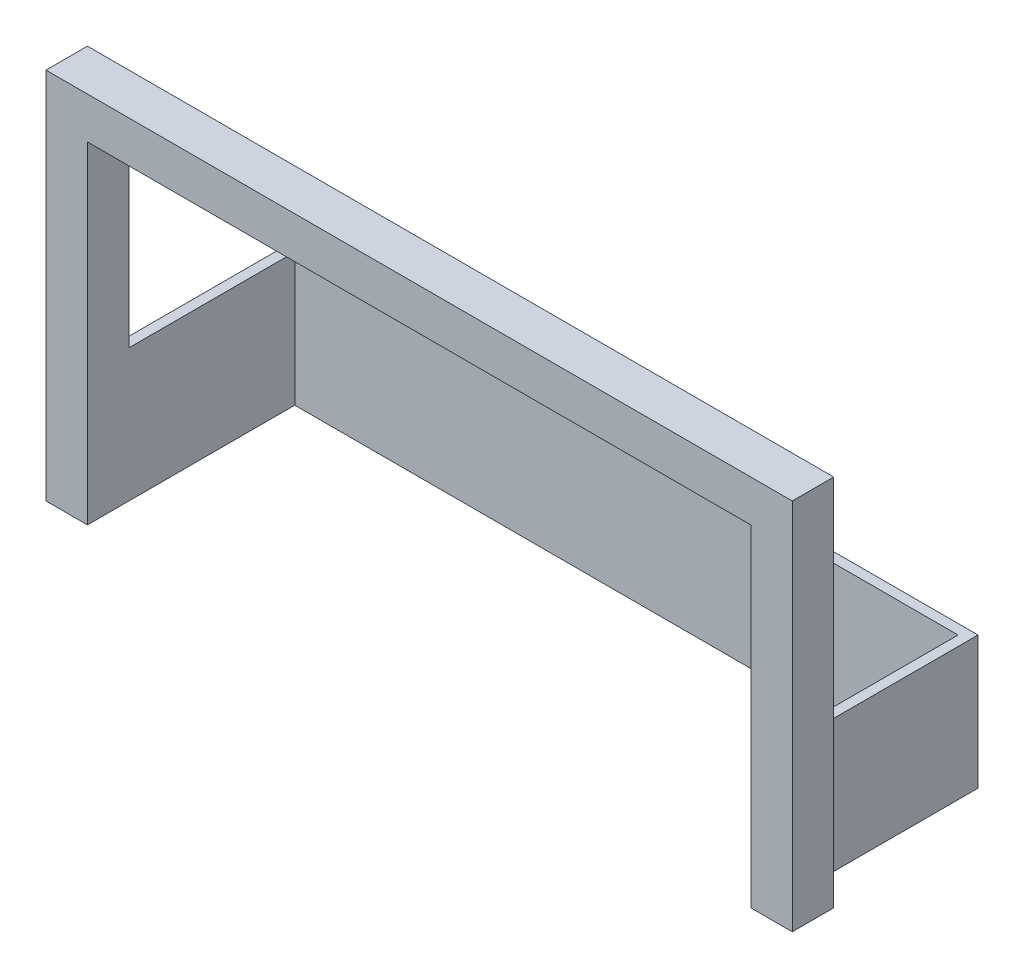
SolidWorks part; units mm, degrees
ref_plane "前视基准面" through (0, 0, 0) normal (0, 0, 1) x (1, 0, 0)
ref_plane "上视基准面" through (0, 0, 0) normal (0, 1, 0) x (1, 0, 0)
ref_plane "右视基准面" through (0, 0, 0) normal (1, 0, 0) x (0, 0, -1)
sketch "草图1" plane through (0, 0, 0) normal (0, 0, 1) x (1, 0, 0)
  line L0 (-1125, 1125) -> (-1125, 0)
  line L1 (-1000, 1000) -> (1000, 1000)
  line L2 (-1000, 1000) -> (-1000, 0)
  line L3 (-1000, 0) -> (1000, 0) construction
  line L4 (1000, 1000) -> (1000, 0)
  line L5 (-1000, 1000) -> (1000, 0) construction
  line L6 (-1000, 0) -> (1000, 1000) construction
  line L7 (-1125, 1125) -> (1125, 1125)
  line L8 (1125, 1125) -> (1125, 0)
  line L9 (-1125, 0) -> (-1000, 0)
  line L10 (1000, 0) -> (1125, 0)
  point P0 (0, 500)
  dimension "D1" = 2000
  dimension "D2" = 1000
  dimension "D3" = 125
extrude "凸台-拉伸1" add sketch "草图1" against normal blind 125
sketch "草图2" plane through (0, 0, 0) normal (0, -1, 0) x (1, 0, 0)
  line L0 (-1000, -125) -> (-1000, -625)
  line L1 (-1000, -625) -> (1000, -625)
  line L2 (1000, -625) -> (1000, -125)
  dimension "D1" = 500
extrude "拉伸-薄壁1" add sketch "草图2" against normal blind 400 thin
